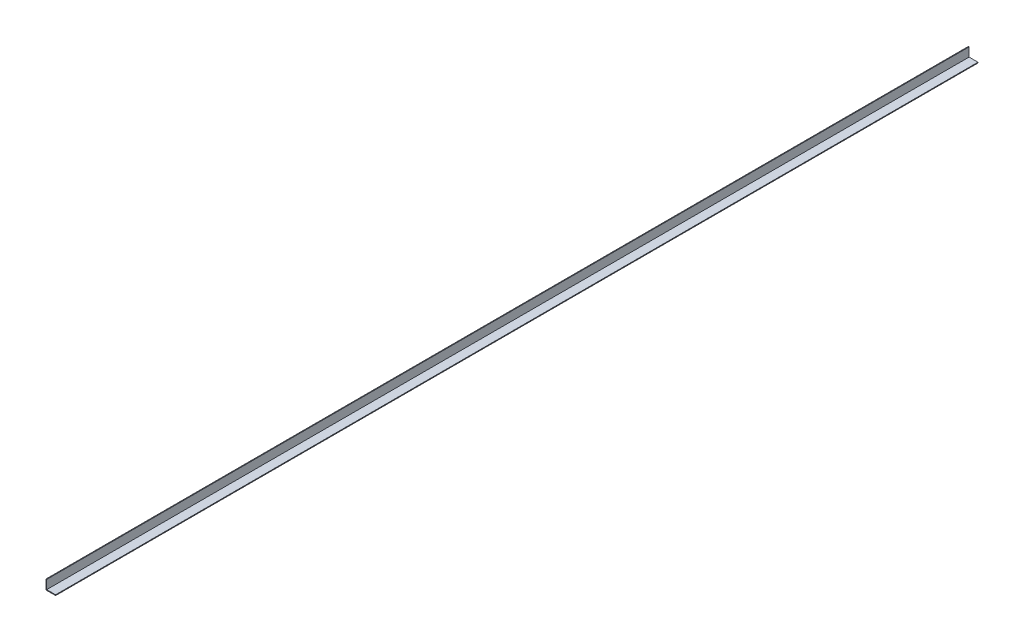
SolidWorks part; units mm, degrees
material "ASTM A36 Acero"
ref_plane "Alzado" through (0, 0, 0) normal (0, 0, 1) x (1, 0, 0)
ref_plane "Planta" through (0, 0, 0) normal (0, 1, 0) x (1, 0, 0)
ref_plane "Vista lateral" through (0, 0, 0) normal (1, 0, 0) x (0, 0, -1)
sketch "Croquis1" plane through (0, 0, 0) normal (0, 0, 1) x (1, 0, 0)
  line L0 (0, 63.5) -> (0, 0)
  line L1 (0, 0) -> (63.5, 0)
  line L2 (63.5, 0) -> (63.5, 4.76)
  line L3 (63.5, 4.76) -> (4.76, 4.76)
  line L4 (4.76, 4.76) -> (4.76, 63.5)
  line L5 (4.76, 63.5) -> (0, 63.5)
  dimension "D1" = 4.76
  dimension "D2" = 63.5
extrude "Saliente-Extruir1" add sketch "Croquis1" against normal blind 6100
